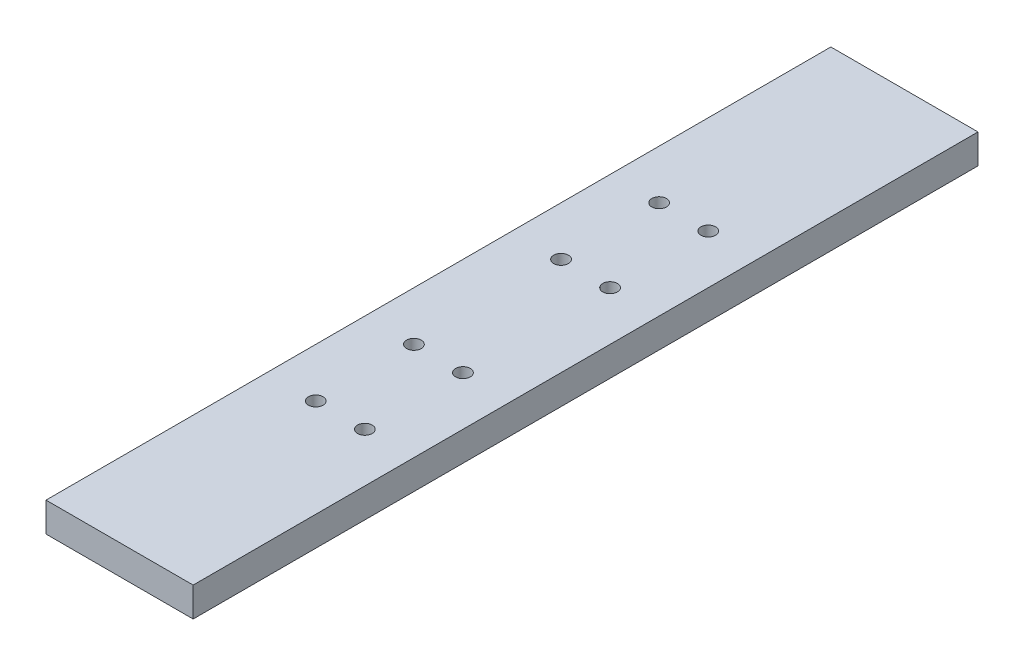
SolidWorks part; units mm, degrees
ref_plane "Front Plane" through (0, 0, 0) normal (0, 0, 1) x (1, 0, 0)
ref_plane "Top Plane" through (0, 0, 0) normal (0, 1, 0) x (1, 0, 0)
ref_plane "Right Plane" through (0, 0, 0) normal (1, 0, 0) x (0, 0, -1)
sketch "Sketch2" plane through (0, 0, 0) normal (0, 0, 1) x (1, 0, 0)
  line L1 (-15, -3) -> (15, -3)
  line L2 (-15, -3) -> (-15, 3)
  line L3 (-15, 3) -> (15, 3)
  line L4 (15, -3) -> (15, 3)
  line L5 (0, 3) -> (0, -3) construction
  line L6 (-15, 0) -> (15, 0) construction
  point P0 (0, 0)
  dimension "D1" = 6
  dimension "D2" = 30
extrude "Boss-Extrude1" add sketch "Sketch2" along normal blind 160
sketch "Sketch3" plane through (0, 3, 0) normal (0, 1, 0) x (1, 0, 0)
  line L0 (-15, -80) -> (15, -80) construction
  line L1 (-15, -160) -> (-15, 0) construction
  line L2 (15, -160) -> (15, 0) construction
  line L3 (-5, -160) -> (-5, -115) construction
  line L4 (15, -160) -> (-15, -160) construction
  line L5 (-5, -115) -> (-15, -115) construction
  circle A0 centre (-5, -115) radius 1.5
  circle A1 centre (5, -115) radius 1.5
  circle A2 centre (5, -95) radius 1.5
  circle A3 centre (-5, -95) radius 1.5
  circle A4 centre (-5, -65) radius 1.5
  circle A5 centre (5, -65) radius 1.5
  circle A6 centre (5, -45) radius 1.5
  circle A7 centre (-5, -45) radius 1.5
  dimension "D3" = 3
  dimension "D4" = 2
  dimension "D5" = 2
  dimension "D1" = 45
  dimension "D2" = 10
extrude "Cut-Extrude3" cut sketch "Sketch3" against normal through all
